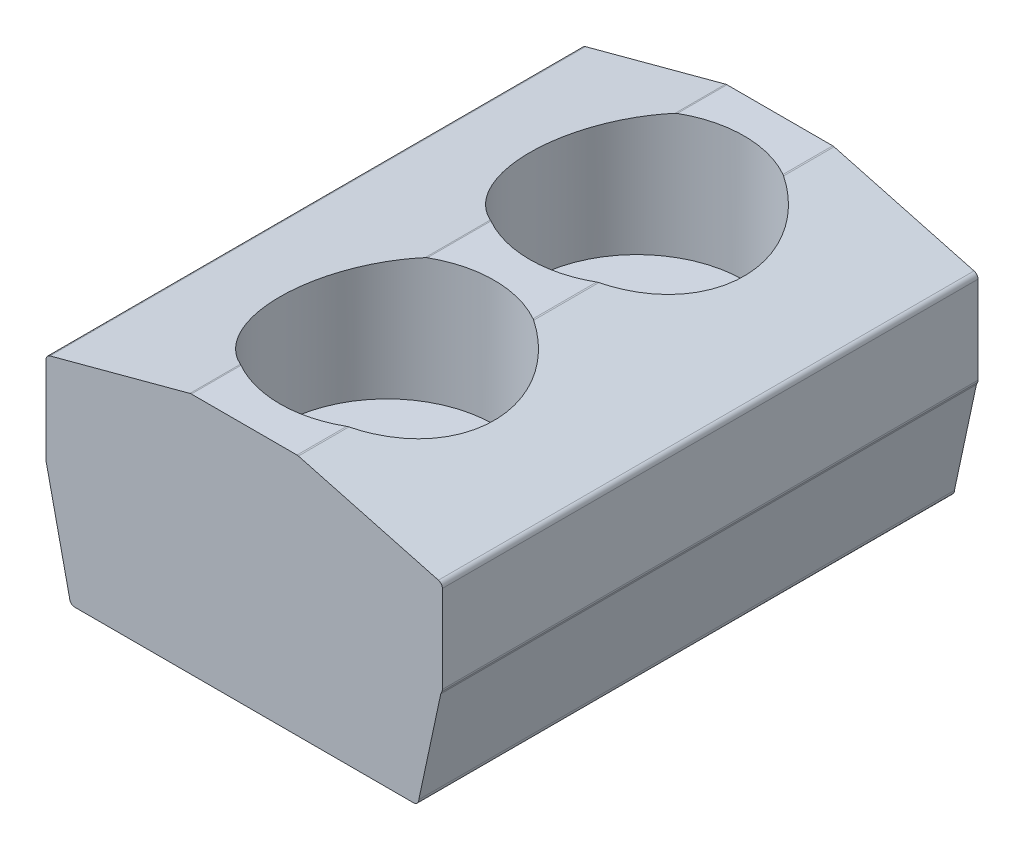
SolidWorks part; units mm, degrees
ref_plane "Front Plane" through (0, 0, 0) normal (0, 0, 1) x (1, 0, 0)
ref_plane "Top Plane" through (0, 0, 0) normal (0, 1, 0) x (1, 0, 0)
ref_plane "Right Plane" through (0, 0, 0) normal (1, 0, 0) x (0, 0, -1)
sketch "Sketch1" plane through (0, 0, 0) normal (0, 0, 1) x (1, 0, 0)
  line L0 (-5.6079, 9.0331) -> (-1.1731, 10.2214)
  line L1 (8.4921, 10.2214) -> (12.9269, 9.0331)
  line L2 (14.6695, 3.1494) -> (13.4399, -2.5944)
  line L3 (-7.4144, 3.2925) -> (-6.1209, -2.5944)
  line L4 (14.5372, 8.6016) -> (12.9269, 9.0331)
  line L5 (8.4921, 10.2214) -> (6.6977, 10.7022)
  line L6 (6.62, 10.7124) -> (0.699, 10.7124)
  line L7 (0.6214, 10.7022) -> (-1.1731, 10.2214)
  line L8 (-5.6079, 9.0331) -> (-7.2181, 8.6016)
  line L9 (-7.4405, 8.3119) -> (-7.4405, 3.4149)
  line L10 (-5.8209, -2.8944) -> (13.1399, -2.8944)
  line L11 (14.6695, 3.1494) -> (14.7334, 3.2925)
  line L12 (14.7595, 3.4149) -> (14.7595, 8.3119)
  arc A0 (6.6977, 10.7022) -> (6.62, 10.7124) centre (6.62, 10.4124) ccw
  arc A1 (0.699, 10.7124) -> (0.6214, 10.7022) centre (0.699, 10.4124) ccw
  arc A2 (-7.2181, 8.6016) -> (-7.4405, 8.3119) centre (-7.1405, 8.3119) ccw
  arc A3 (-7.4405, 3.4149) -> (-7.4144, 3.2925) centre (-7.1405, 3.4149) ccw
  arc A4 (-6.1209, -2.5944) -> (-5.8209, -2.8944) centre (-5.8209, -2.5944) ccw
  arc A5 (13.1399, -2.8944) -> (13.4399, -2.5944) centre (13.1399, -2.5944) ccw
  arc A6 (14.7334, 3.2925) -> (14.7595, 3.4149) centre (14.4595, 3.4149) ccw
  arc A7 (14.7595, 8.3119) -> (14.5372, 8.6016) centre (14.4595, 8.3119) ccw
extrude "Boss-Extrude1" add sketch "Sketch1" along normal blind 30
sketch "Sketch2" plane through (0, -2.8944, 0) normal (0, -1, 0) x (1, 0, 0)
  line L0 (-5.8209, 30) -> (13.1399, 30) construction
  line L1 (13.1399, 30) -> (3.6595, 30) construction
  line L2 (3.6595, 30) -> (3.6595, 0) construction
  line L3 (-5.8209, 0) -> (13.1399, 0) construction
  circle A1 centre (3.6595, 22) radius 3.2
  circle A3 centre (3.6595, 8) radius 3.2
  point P12 (3.6595, 8.3685)
  point P13 (3.6595, 0.3124)
  point P14 (3.6595, 0)
  point P17 (3.6595, 21.5177)
  point P18 (0, 0)
  dimension "D2" = 6.4
  dimension "D3" = 6.4
  dimension "D5" = 8
  dimension "D6" = 8
extrude "Cut-Extrude3" cut sketch "Sketch2" against normal through all
sketch "Sketch4" plane through (0, 10.7124, 0) normal (0, 1, 0) x (1, 0, 0)
  circle A0 centre (3.6595, -8) radius 6
  circle A1 centre (3.6595, -22) radius 6
  dimension "D1" = 12
  dimension "D2" = 12
extrude "Cut-Extrude4" cut sketch "Sketch4" against normal blind 7
equation "\"D2@Sketch4\"=\"D1@Sketch4\""
